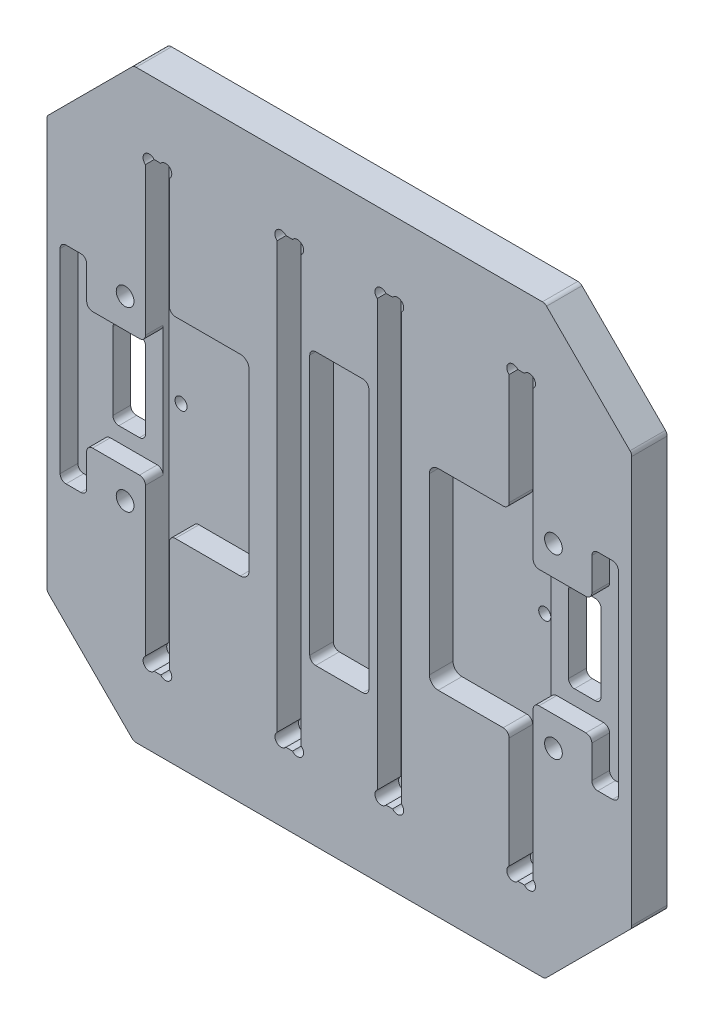
SolidWorks part; units mm, degrees
ref_plane "Front" through (0, 0, 0) normal (0, 0, 1) x (1, 0, 0)
ref_plane "Top" through (0, 0, 0) normal (0, 1, 0) x (1, 0, 0)
ref_plane "Right" through (0, 0, 0) normal (1, 0, 0) x (0, 0, -1)
sketch "Esquisse2" plane through (0, 0, 0) normal (0, 0, 1) x (1, 0, 0)
  line L1 (0, 0) -> (200, 0)
  line L2 (0, 0) -> (0, 200)
  line L3 (0, 200) -> (200, 200)
  line L4 (200, 0) -> (200, 200)
  dimension "D1" = 200
  dimension "D2" = 200
extrude "Boss.-Extru.1" add sketch "Esquisse2" along normal blind 12
sketch "Esquisse3" plane through (0, 0, 12) normal (0, 0, 1) x (1, 0, 0)
  line L0 (0, 100) -> (200, 100) construction
  line L1 (0, 200) -> (0, 0) construction
  line L2 (200, 0) -> (200, 200) construction
  line L3 (0, 0) -> (200, 0) construction
  line L4 (100, 100) -> (100, 198.2097) construction
  line L5 (185.5, 67) -> (185.5, 133)
  line L6 (187.5, 135) -> (192.5, 135)
  line L7 (194.5, 133) -> (194.5, 67)
  line L8 (187.5, 65) -> (192.5, 65)
  line L9 (12.5, 65) -> (7.5, 65)
  line L10 (5.5, 133) -> (5.5, 67)
  line L11 (12.5, 135) -> (7.5, 135)
  line L12 (14.5, 67) -> (14.5, 133)
  line L13 (69.5, 70.5) -> (69.5, 129.5)
  line L14 (66.5, 132.5) -> (45.5, 132.5)
  line L15 (42.5, 129.5) -> (42.5, 70.5)
  line L16 (190, 135) -> (190, 163.9784) construction
  line L17 (190, 163.9784) -> (100, 163.9784) construction
  line L18 (56, 132.5) -> (56, 150.9164) construction
  line L19 (56, 150.9164) -> (100, 150.9164) construction
  line L20 (66.5, 67.5) -> (45.5, 67.5)
  line L21 (133.5, 67.5) -> (154.5, 67.5)
  line L22 (157.5, 129.5) -> (157.5, 70.5)
  line L23 (133.5, 132.5) -> (154.5, 132.5)
  line L24 (130.5, 70.5) -> (130.5, 129.5)
  circle A0 centre (172.5, 130) radius 3
  circle A1 centre (172.5, 70) radius 3
  circle A2 centre (27.5, 70) radius 3
  circle A3 centre (27.5, 130) radius 3
  arc A4 (192.5, 65) -> (194.5, 67) centre (192.5, 67) ccw
  arc A5 (187.5, 65) -> (185.5, 67) centre (187.5, 67) cw
  arc A6 (192.5, 135) -> (194.5, 133) centre (192.5, 133) cw
  arc A7 (185.5, 133) -> (187.5, 135) centre (187.5, 133) cw
  arc A8 (12.5, 65) -> (14.5, 67) centre (12.5, 67) ccw
  arc A9 (7.5, 65) -> (5.5, 67) centre (7.5, 67) cw
  arc A10 (12.5, 135) -> (14.5, 133) centre (12.5, 133) cw
  arc A11 (5.5, 133) -> (7.5, 135) centre (7.5, 133) cw
  arc A12 (133.5, 67.5) -> (130.5, 70.5) centre (133.5, 70.5) cw
  arc A13 (154.5, 67.5) -> (157.5, 70.5) centre (154.5, 70.5) ccw
  arc A14 (157.5, 129.5) -> (154.5, 132.5) centre (154.5, 129.5) ccw
  arc A15 (133.5, 132.5) -> (130.5, 129.5) centre (133.5, 129.5) ccw
  arc A16 (66.5, 67.5) -> (69.5, 70.5) centre (66.5, 70.5) ccw
  arc A17 (45.5, 67.5) -> (42.5, 70.5) centre (45.5, 70.5) cw
  arc A18 (69.5, 129.5) -> (66.5, 132.5) centre (66.5, 129.5) ccw
  arc A19 (45.5, 132.5) -> (42.5, 129.5) centre (45.5, 129.5) ccw
  point P23 (194.5, 100)
  point P24 (185.5, 100)
  point P28 (14.5, 100)
  point P29 (5.5, 100)
  point P41 (42.5, 100)
  point P42 (69.5, 100)
  point P46 (130.5, 100)
  point P47 (157.5, 100)
  point P50 (194.5, 65)
  point P53 (185.5, 65)
  point P56 (194.5, 135)
  point P59 (185.5, 135)
  point P62 (14.5, 65)
  point P65 (5.5, 65)
  point P68 (14.5, 135)
  point P71 (5.5, 135)
  point P74 (130.5, 67.5)
  point P77 (157.5, 67.5)
  point P80 (157.5, 132.5)
  point P83 (130.5, 132.5)
  point P86 (69.5, 67.5)
  point P89 (42.5, 67.5)
  point P92 (69.5, 132.5)
  point P95 (42.5, 132.5)
  dimension "D2" = 60
  dimension "D3" = 44
  dimension "D4" = 6
  dimension "D11" = 2
  dimension "D12" = 3
  dimension "D1" = 100
  dimension "D5" = 9
  dimension "D6" = 13
  dimension "D7" = 70
  dimension "D8" = 90
  dimension "D9" = 65
  dimension "D10" = 27
extrude "Enlèv. mat.-Extru.1" cut sketch "Esquisse3" against normal through all both and the other way through all
chamfer "Chanfrein1" distance 30 distance2 30 4 edges at (0, 200, 6) (200, 200, 6) (200, 0, 6) (0, 0, 6)
sketch "Esquisse4" plane through (0, 0, 12) normal (0, 0, 1) x (1, 0, 0)
  line L16 (169.5858, 199) -> (30.4142, 199)
  line L17 (30.4142, 199) -> (1, 169.5858)
  line L18 (1, 169.5858) -> (1, 30.4142)
  line L19 (1, 30.4142) -> (30.4142, 1)
  line L20 (30.4142, 1) -> (169.5858, 1)
  line L21 (169.5858, 1) -> (199, 30.4142)
  line L22 (199, 30.4142) -> (199, 169.5858)
  line L23 (199, 169.5858) -> (169.5858, 199)
  line L24 (169.5858, 199) -> (30.4142, 199)
  line L25 (30.4142, 199) -> (1, 169.5858)
  line L26 (1, 169.5858) -> (1, 30.4142)
  line L27 (1, 30.4142) -> (30.4142, 1)
  line L28 (30.4142, 1) -> (169.5858, 1)
  line L29 (169.5858, 1) -> (199, 30.4142)
  line L30 (199, 30.4142) -> (199, 169.5858)
  line L31 (199, 169.5858) -> (169.5858, 199)
  line L32 (170, 200) -> (30, 200)
  line L33 (30, 200) -> (0, 170)
  line L34 (0, 170) -> (0, 30)
  line L35 (0, 30) -> (30, 0)
  line L36 (30, 0) -> (170, 0)
  line L37 (170, 0) -> (200, 30)
  line L38 (200, 30) -> (200, 170)
  line L39 (200, 170) -> (170, 200)
  line L40 (170, 200) -> (30, 200)
  line L41 (30, 200) -> (0, 170)
  line L42 (0, 170) -> (0, 30)
  line L43 (0, 30) -> (30, 0)
  line L44 (30, 0) -> (170, 0)
  line L45 (170, 0) -> (200, 30)
  line L46 (200, 30) -> (200, 170)
  line L47 (200, 170) -> (170, 200)
  dimension "D1" = 1
  dimension "D2" = 0
extrude "Enlèv. mat.-Extru.2" cut sketch "Esquisse4" against normal blind 10
sketch "Esquisse5" plane through (0, 0, 12) normal (0, 0, 1) x (1, 0, 0)
  line L0 (100, 0) -> (100, 100) construction
  line L1 (14.5, 120) -> (14.5, 80)
  line L2 (165.5, 120) -> (185.5, 120)
  line L3 (165.5, 120) -> (165.5, 80)
  line L4 (165.5, 80) -> (185.5, 80)
  line L5 (30, 0) -> (170, 0) construction
  line L6 (100, 100) -> (165.5, 100) construction
  line L7 (185.5, 120) -> (185.5, 80)
  line L8 (100, 100) -> (69.5, 100) construction
  line L9 (69.5, 70.5) -> (69.5, 129.5) construction
  line L10 (34.5, 80) -> (14.5, 80)
  line L11 (34.5, 120) -> (34.5, 80)
  line L12 (34.5, 120) -> (14.5, 120)
  dimension "D1" = 40
  dimension "D2" = 65.5
  dimension "D3" = 20
extrude "Enlèv. mat.-Extru.3" cut sketch "Esquisse5" against normal blind 6
sketch "Esquisse6" plane through (0, 0, 12) normal (0, 0, 1) x (1, 0, 0)
  line L0 (69.5, 100) -> (130.5, 100) construction
  line L1 (157.5, 175) -> (165.62, 175)
  line L2 (157.5, 175) -> (157.5, 25)
  line L3 (157.5, 25) -> (165.62, 25)
  line L4 (165.62, 175) -> (165.62, 25)
  line L5 (69.5, 70.5) -> (69.5, 129.5) construction
  line L6 (130.5, 129.5) -> (130.5, 70.5) construction
  line L7 (100, 100) -> (100, 191.362) construction
  line L8 (130.5, 100) -> (157.5, 100) construction
  line L9 (157.5, 70.5) -> (157.5, 129.5) construction
  line L10 (34.38, 175) -> (34.38, 25)
  line L11 (42.5, 25) -> (34.38, 25)
  line L12 (42.5, 175) -> (42.5, 25)
  line L13 (42.5, 175) -> (34.38, 175)
  line L14 (112.88, 100) -> (100, 100) construction
  line L15 (112.88, 175) -> (121, 175)
  line L16 (112.88, 175) -> (112.88, 25)
  line L17 (112.88, 25) -> (121, 25)
  line L18 (121, 175) -> (121, 25)
  line L19 (79, 175) -> (79, 25)
  line L20 (87.12, 25) -> (79, 25)
  line L21 (87.12, 175) -> (87.12, 25)
  line L22 (87.12, 175) -> (79, 175)
  dimension "D1" = 150
  dimension "D2" = 8.12
  dimension "D3" = 8.12
  dimension "D4" = 150
  dimension "D5" = 21
extrude "Enlèv. mat.-Extru.4" cut sketch "Esquisse6" against normal blind 8
sketch "Esquisse7" plane through (0, 0, 12) normal (0, 0, 1) x (1, 0, 0)
  line L0 (87.12, 100) -> (112.88, 100) construction
  line L1 (87.12, 25) -> (87.12, 175) construction
  line L2 (112.88, 175) -> (112.88, 25) construction
  line L3 (100, 100) -> (100, 199) construction
  line L4 (169.5858, 199) -> (30.4142, 199) construction
  line L5 (114.18, 173.7) -> (112.88, 175) construction
  line L6 (121, 175) -> (112.88, 175) construction
  line L7 (116.94, 175) -> (116.94, 100) construction
  line L8 (121, 175) -> (112.88, 175) construction
  line L9 (116.94, 100) -> (112.88, 100) construction
  line L10 (119.7, 173.7) -> (121, 175) construction
  line L11 (119.7, 26.3) -> (121, 25) construction
  line L12 (114.18, 26.3) -> (112.88, 25) construction
  line L13 (116.94, 100) -> (139.25, 100) construction
  line L14 (139.25, 100) -> (139.25, 192.3771) construction
  line L15 (164.32, 26.3) -> (165.62, 25) construction
  line L16 (158.8, 26.3) -> (157.5, 25) construction
  line L17 (158.8, 173.7) -> (157.5, 175) construction
  line L18 (161.56, 100) -> (165.62, 100) construction
  line L19 (161.56, 175) -> (161.56, 100) construction
  line L20 (164.32, 173.7) -> (165.62, 175) construction
  line L21 (165.62, 175) -> (157.5, 175) construction
  line L22 (35.68, 173.7) -> (34.38, 175) construction
  line L23 (38.44, 175) -> (38.44, 100) construction
  line L24 (38.44, 100) -> (34.38, 100) construction
  line L25 (41.2, 173.7) -> (42.5, 175) construction
  line L26 (41.2, 26.3) -> (42.5, 25) construction
  line L27 (35.68, 26.3) -> (34.38, 25) construction
  line L28 (60.75, 100) -> (60.75, 192.3771) construction
  line L29 (83.06, 100) -> (60.75, 100) construction
  line L30 (85.82, 26.3) -> (87.12, 25) construction
  line L31 (80.3, 26.3) -> (79, 25) construction
  line L32 (80.3, 173.7) -> (79, 175) construction
  line L33 (83.06, 100) -> (87.12, 100) construction
  line L34 (83.06, 175) -> (83.06, 100) construction
  line L35 (85.82, 173.7) -> (87.12, 175) construction
  circle A0 centre (114.18, 173.7) radius 2.1
  circle A1 centre (119.7, 173.7) radius 2.1
  circle A2 centre (119.7, 26.3) radius 2.1
  circle A3 centre (114.18, 26.3) radius 2.1
  circle A4 centre (164.32, 26.3) radius 2.1
  circle A5 centre (158.8, 26.3) radius 2.1
  circle A6 centre (158.8, 173.7) radius 2.1
  circle A7 centre (164.32, 173.7) radius 2.1
  circle A8 centre (35.68, 173.7) radius 2.1
  circle A9 centre (41.2, 173.7) radius 2.1
  circle A10 centre (41.2, 26.3) radius 2.1
  circle A11 centre (35.68, 26.3) radius 2.1
  circle A12 centre (85.82, 26.3) radius 2.1
  circle A13 centre (80.3, 26.3) radius 2.1
  circle A14 centre (80.3, 173.7) radius 2.1
  circle A15 centre (85.82, 173.7) radius 2.1
  dimension "D1" = 4.2
  dimension "D2" = 1.3
  dimension "D3" = 1.3
extrude "Enlèv. mat.-Extru.5" cut sketch "Esquisse7" against normal up to vertex (8 mm away) up to point (112.88, 25, 4)
sketch "Esquisse8" plane through (0, 0, 12) normal (0, 0, 1) x (1, 0, 0)
  line L0 (100, 1) -> (100, 199) construction
  line L1 (30.4142, 1) -> (169.5858, 1) construction
  line L2 (169.5858, 199) -> (30.4142, 199) construction
  line L3 (100, 100) -> (252.8445, 100) construction
  line L4 (110, 54) -> (110, 146)
  line L5 (110, 146) -> (90, 146)
  line L6 (90, 54) -> (90, 146)
  line L7 (110, 54) -> (90, 54)
  point P8 (100, 54)
  point P12 (100, 146)
  point P14 (90, 100)
  point P15 (110, 100)
  dimension "D1" = 20
  dimension "D2" = 92
extrude "Enlèv. mat.-Extru.6" cut sketch "Esquisse8" against normal blind 8
sketch "Esquisse10" plane through (0, 0, 12) normal (0, 0, 1) x (1, 0, 0)
  line L0 (45.5, 132.5) -> (42.5, 132.5)
  line L1 (42.5, 129.5) -> (42.5, 172.0508) construction
  line L2 (42.5, 132.5) -> (42.5, 129.5)
  line L3 (42.5, 129.5) -> (45.5, 132.5)
  line L4 (42.5, 100) -> (69.5, 100) construction
  line L5 (42.5, 70.5) -> (42.5, 129.5) construction
  line L6 (69.5, 70.5) -> (69.5, 129.5) construction
  line L7 (100, 54) -> (100, 146) construction
  line L8 (90, 54) -> (110, 54) construction
  line L9 (110, 146) -> (90, 146) construction
  line L10 (42.5, 70.5) -> (45.5, 67.5)
  line L11 (42.5, 67.5) -> (42.5, 70.5)
  line L12 (45.5, 67.5) -> (42.5, 67.5)
  line L13 (154.5, 67.5) -> (157.5, 67.5)
  line L14 (157.5, 67.5) -> (157.5, 70.5)
  line L15 (157.5, 70.5) -> (154.5, 67.5)
  line L16 (157.5, 129.5) -> (154.5, 132.5)
  line L17 (157.5, 132.5) -> (157.5, 129.5)
  line L18 (154.5, 132.5) -> (157.5, 132.5)
extrude "Enlèv. mat.-Extru.8" cut sketch "Esquisse10" against normal up to vertex
sketch "Esquisse11" plane through (0, 0, 6) normal (0, 0, 1) x (1, 0, 0)
  line L0 (28.38, 100) -> (34.38, 100) construction
  line L1 (17.38, 115) -> (28.38, 115)
  line L2 (17.38, 115) -> (17.38, 85)
  line L3 (17.38, 85) -> (28.38, 85)
  line L4 (28.38, 115) -> (28.38, 85)
  line L5 (34.38, 120) -> (34.38, 80) construction
  line L6 (100, 1) -> (100, 159.2856) construction
  line L7 (30.4142, 1) -> (169.5858, 1) construction
  line L8 (171.62, 115) -> (171.62, 85)
  line L9 (182.62, 85) -> (171.62, 85)
  line L10 (182.62, 115) -> (182.62, 85)
  line L11 (182.62, 115) -> (171.62, 115)
  dimension "D1" = 6
  dimension "D2" = 11
  dimension "D3" = 30
extrude "Enlèv. mat.-Extru.9" cut sketch "Esquisse11" against normal through all both and the other way through all
fillet "Congé1" radius 2 16 edges at (110, 54, 8) (90, 54, 8) (110, 146, 8) (90, 146, 8) (165.62, 120, 9) (185.5, 120, 9) (185.5, 80, 9) (165.62, 80, 9) (34.38, 80, 9) (14.5, 80, 9) (34.38, 120, 9) (14.5, 120, 9) (42.5, 67.5, 8) (42.5, 132.5, 8) (157.5, 132.5, 8) (157.5, 67.5, 8)
fillet "Congé2" radius 2 16 edges at (1, 169.5858, 7) (30.4142, 199, 7) (169.5858, 199, 7) (199, 169.5858, 7) (199, 30.4142, 7) (169.5858, 1, 7) (1, 30.4142, 7) (30.4142, 1, 7) (170, 200, 1) (200, 170, 1) (200, 30, 1) (170, 0, 1) (30, 0, 1) (0, 30, 1) (0, 170, 1) (30, 200, 1)
sketch "Esquisse9" plane through (0, 0, 12) normal (0, 0, 1) x (1, 0, 0)
  line L0 (22.7574, 205.4853) -> (-5.4853, 177.2426)
  line L1 (-9, 168.7574) -> (-9, 31.2426)
  line L2 (-5.4853, 22.7574) -> (22.7574, -5.4853)
  line L3 (31.2426, -9) -> (168.7574, -9)
  line L4 (177.2426, -5.4853) -> (205.4853, 22.7574)
  line L5 (209, 31.2426) -> (209, 168.7574)
  line L6 (205.4853, 177.2426) -> (177.2426, 205.4853)
  line L7 (168.7574, 209) -> (31.2426, 209)
  line L8 (29.8284, 198.4142) -> (1.5858, 170.1716)
  line L9 (1, 168.7574) -> (1, 31.2426)
  line L10 (1.5858, 29.8284) -> (29.8284, 1.5858)
  line L11 (31.2426, 1) -> (168.7574, 1)
  line L12 (170.1716, 1.5858) -> (198.4142, 29.8284)
  line L13 (199, 31.2426) -> (199, 168.7574)
  line L14 (198.4142, 170.1716) -> (170.1716, 198.4142)
  line L15 (168.7574, 199) -> (31.2426, 199)
  line L16 (29.8284, 198.4142) -> (1.5858, 170.1716)
  line L17 (1, 168.7574) -> (1, 31.2426)
  line L18 (1.5858, 29.8284) -> (29.8284, 1.5858)
  line L19 (31.2426, 1) -> (168.7574, 1)
  line L20 (170.1716, 1.5858) -> (198.4142, 29.8284)
  line L21 (199, 31.2426) -> (199, 168.7574)
  line L22 (198.4142, 170.1716) -> (170.1716, 198.4142)
  line L23 (168.7574, 199) -> (31.2426, 199)
  arc A0 (-5.4853, 177.2426) -> (-9, 168.7574) centre (3, 168.7574) ccw
  arc A1 (-9, 31.2426) -> (-5.4853, 22.7574) centre (3, 31.2426) ccw
  arc A2 (22.7574, -5.4853) -> (31.2426, -9) centre (31.2426, 3) ccw
  arc A3 (168.7574, -9) -> (177.2426, -5.4853) centre (168.7574, 3) ccw
  arc A4 (205.4853, 22.7574) -> (209, 31.2426) centre (197, 31.2426) ccw
  arc A5 (209, 168.7574) -> (205.4853, 177.2426) centre (197, 168.7574) ccw
  arc A6 (177.2426, 205.4853) -> (168.7574, 209) centre (168.7574, 197) ccw
  arc A7 (31.2426, 209) -> (22.7574, 205.4853) centre (31.2426, 197) ccw
  arc A8 (1.5858, 170.1716) -> (1, 168.7574) centre (3, 168.7574) ccw
  arc A9 (1, 31.2426) -> (1.5858, 29.8284) centre (3, 31.2426) ccw
  arc A10 (29.8284, 1.5858) -> (31.2426, 1) centre (31.2426, 3) ccw
  arc A11 (168.7574, 1) -> (170.1716, 1.5858) centre (168.7574, 3) ccw
  arc A12 (198.4142, 29.8284) -> (199, 31.2426) centre (197, 31.2426) ccw
  arc A13 (199, 168.7574) -> (198.4142, 170.1716) centre (197, 168.7574) ccw
  arc A14 (170.1716, 198.4142) -> (168.7574, 199) centre (168.7574, 197) ccw
  arc A15 (31.2426, 199) -> (29.8284, 198.4142) centre (31.2426, 197) ccw
  arc A16 (1.5858, 170.1716) -> (1, 168.7574) centre (3, 168.7574) ccw
  arc A17 (1, 31.2426) -> (1.5858, 29.8284) centre (3, 31.2426) ccw
  arc A18 (29.8284, 1.5858) -> (31.2426, 1) centre (31.2426, 3) ccw
  arc A19 (168.7574, 1) -> (170.1716, 1.5858) centre (168.7574, 3) ccw
  arc A20 (198.4142, 29.8284) -> (199, 31.2426) centre (197, 31.2426) ccw
  arc A21 (199, 168.7574) -> (198.4142, 170.1716) centre (197, 168.7574) ccw
  arc A22 (170.1716, 198.4142) -> (168.7574, 199) centre (168.7574, 197) ccw
  arc A23 (31.2426, 199) -> (29.8284, 198.4142) centre (31.2426, 197) ccw
  dimension "D1" = 0
  dimension "D2" = 10
extrude "Enlèv. mat.-Extru.7" cut sketch "Esquisse9" against normal through all both and the other way through all
fillet "Congé3" radius 2 8 edges at (182.62, 85, 3) (171.62, 85, 3) (182.62, 115, 3) (171.62, 115, 3) (17.38, 115, 3) (28.38, 115, 3) (28.38, 85, 3) (17.38, 85, 3)
sketch "Esquisse12" plane through (0, 0, 0) normal (0, 0, -1) x (-1, 0, 0)
  line L0 (-69.5, 70.5) -> (-69.5, 129.5) construction
  line L1 (-66.5, 132.5) -> (-45.5, 132.5) construction
  line L2 (-42.5, 129.5) -> (-42.5, 70.5) construction
  line L3 (-45.5, 67.5) -> (-66.5, 67.5) construction
  line L4 (-133.5, 67.5) -> (-154.5, 67.5) construction
  line L5 (-130.5, 129.5) -> (-130.5, 70.5) construction
  line L6 (-154.5, 132.5) -> (-133.5, 132.5) construction
  line L7 (-157.5, 70.5) -> (-157.5, 129.5) construction
  line L8 (-69.5, 70.5) -> (-69.5, 129.5)
  line L9 (-66.5, 132.5) -> (-45.5, 132.5)
  line L10 (-42.5, 129.5) -> (-42.5, 70.5)
  line L11 (-45.5, 67.5) -> (-66.5, 67.5)
  line L12 (-133.5, 67.5) -> (-154.5, 67.5)
  line L13 (-130.5, 129.5) -> (-130.5, 70.5)
  line L14 (-154.5, 132.5) -> (-133.5, 132.5)
  line L15 (-157.5, 70.5) -> (-157.5, 129.5)
  arc A0 (-66.5, 132.5) -> (-69.5, 129.5) centre (-66.5, 129.5) ccw construction
  arc A1 (-42.5, 129.5) -> (-45.5, 132.5) centre (-45.5, 129.5) ccw construction
  arc A2 (-45.5, 67.5) -> (-42.5, 70.5) centre (-45.5, 70.5) ccw construction
  arc A3 (-69.5, 70.5) -> (-66.5, 67.5) centre (-66.5, 70.5) ccw construction
  arc A4 (-157.5, 70.5) -> (-154.5, 67.5) centre (-154.5, 70.5) ccw construction
  arc A5 (-133.5, 67.5) -> (-130.5, 70.5) centre (-133.5, 70.5) ccw construction
  arc A6 (-130.5, 129.5) -> (-133.5, 132.5) centre (-133.5, 129.5) ccw construction
  arc A7 (-154.5, 132.5) -> (-157.5, 129.5) centre (-154.5, 129.5) ccw construction
  arc A8 (-66.5, 132.5) -> (-69.5, 129.5) centre (-66.5, 129.5) ccw
  arc A9 (-42.5, 129.5) -> (-45.5, 132.5) centre (-45.5, 129.5) ccw
  arc A10 (-45.5, 67.5) -> (-42.5, 70.5) centre (-45.5, 70.5) ccw
  arc A11 (-69.5, 70.5) -> (-66.5, 67.5) centre (-66.5, 70.5) ccw
  arc A12 (-157.5, 70.5) -> (-154.5, 67.5) centre (-154.5, 70.5) ccw
  arc A13 (-133.5, 67.5) -> (-130.5, 70.5) centre (-133.5, 70.5) ccw
  arc A14 (-130.5, 129.5) -> (-133.5, 132.5) centre (-133.5, 129.5) ccw
  arc A15 (-154.5, 132.5) -> (-157.5, 129.5) centre (-154.5, 129.5) ccw
extrude "Boss.-Extru.2" add sketch "Esquisse12" against normal up to vertex
sketch "Esquisse13" plane through (0, 0, 0) normal (0, 0, -1) x (-1, 0, 0)
  line L0 (-14.5, 67) -> (-14.5, 133) construction
  line L1 (-12.5, 135) -> (-7.5, 135) construction
  line L2 (-5.5, 133) -> (-5.5, 67) construction
  line L3 (-7.5, 65) -> (-12.5, 65) construction
  line L4 (-187.5, 65) -> (-192.5, 65) construction
  line L5 (-194.5, 67) -> (-194.5, 133) construction
  line L6 (-192.5, 135) -> (-187.5, 135) construction
  line L7 (-185.5, 133) -> (-185.5, 67) construction
  line L8 (-14.5, 67) -> (-14.5, 133)
  line L9 (-12.5, 135) -> (-7.5, 135)
  line L10 (-5.5, 133) -> (-5.5, 67)
  line L11 (-7.5, 65) -> (-12.5, 65)
  line L12 (-187.5, 65) -> (-192.5, 65)
  line L13 (-194.5, 67) -> (-194.5, 133)
  line L14 (-192.5, 135) -> (-187.5, 135)
  line L15 (-185.5, 133) -> (-185.5, 67)
  arc A0 (-14.5, 67) -> (-12.5, 65) centre (-12.5, 67) ccw construction
  arc A1 (-12.5, 135) -> (-14.5, 133) centre (-12.5, 133) ccw construction
  arc A2 (-5.5, 133) -> (-7.5, 135) centre (-7.5, 133) ccw construction
  arc A3 (-7.5, 65) -> (-5.5, 67) centre (-7.5, 67) ccw construction
  arc A4 (-187.5, 65) -> (-185.5, 67) centre (-187.5, 67) ccw construction
  arc A5 (-194.5, 67) -> (-192.5, 65) centre (-192.5, 67) ccw construction
  arc A6 (-192.5, 135) -> (-194.5, 133) centre (-192.5, 133) ccw construction
  arc A7 (-185.5, 133) -> (-187.5, 135) centre (-187.5, 133) ccw construction
  arc A8 (-14.5, 67) -> (-12.5, 65) centre (-12.5, 67) ccw
  arc A9 (-12.5, 135) -> (-14.5, 133) centre (-12.5, 133) ccw
  arc A10 (-5.5, 133) -> (-7.5, 135) centre (-7.5, 133) ccw
  arc A11 (-7.5, 65) -> (-5.5, 67) centre (-7.5, 67) ccw
  arc A12 (-187.5, 65) -> (-185.5, 67) centre (-187.5, 67) ccw
  arc A13 (-194.5, 67) -> (-192.5, 65) centre (-192.5, 67) ccw
  arc A14 (-192.5, 135) -> (-194.5, 133) centre (-192.5, 133) ccw
  arc A15 (-185.5, 133) -> (-187.5, 135) centre (-187.5, 133) ccw
extrude "Boss.-Extru.3" add sketch "Esquisse13" against normal up to vertex (6 mm away) up to point (14.5, 78, 6)
sketch "Esquisse14" plane through (0, 0, 4) normal (0, 0, 1) x (1, 0, 0)
  line L0 (100, 54) -> (100, 146) construction
  line L1 (92, 54) -> (108, 54) construction
  line L2 (108, 146) -> (92, 146) construction
  line L3 (100, 100) -> (-15.2006, 100) construction
  line L4 (83.06, 160) -> (83.06, 175) construction
  line L5 (84.1708, 175) -> (81.9492, 175) construction
  line L7 (79, 150.5938) -> (42.5, 150.5938) construction
  line L8 (79, 172.0508) -> (79, 27.9492) construction
  line L9 (42.5, 134.5) -> (42.5, 172.0508) construction
  line L10 (60.75, 150.5938) -> (60.75, 164.7943) construction
  line L11 (83.06, 100) -> (83.06, 40) construction
  line L12 (38.44, 100) -> (38.44, 40) construction
  line L13 (38.44, 160) -> (38.44, 175) construction
  line L14 (161.56, 160) -> (161.56, 175) construction
  line L15 (161.56, 100) -> (161.56, 40) construction
  line L16 (116.94, 100) -> (116.94, 40) construction
  line L17 (139.25, 150.5938) -> (139.25, 164.7943) construction
  line L18 (121, 150.5938) -> (157.5, 150.5938) construction
  line L19 (116.94, 160) -> (116.94, 175) construction
  circle A0 centre (83.06, 160) radius 2.05
  circle A1 centre (83.06, 40) radius 2.05
  circle A2 centre (83.06, 100) radius 2.05
  circle A3 centre (38.44, 100) radius 2.05
  circle A4 centre (38.44, 40) radius 2.05
  circle A5 centre (38.44, 160) radius 2.05
  circle A6 centre (161.56, 160) radius 2.05
  circle A7 centre (161.56, 40) radius 2.05
  circle A8 centre (161.56, 100) radius 2.05
  circle A9 centre (116.94, 100) radius 2.05
  circle A10 centre (116.94, 40) radius 2.05
  circle A11 centre (116.94, 160) radius 2.05
  dimension "D1" = 60
  dimension "D2" = 4.1
extrude "Enlèv. mat.-Extru.10" cut sketch "Esquisse14" against normal through all both and the other way through all
